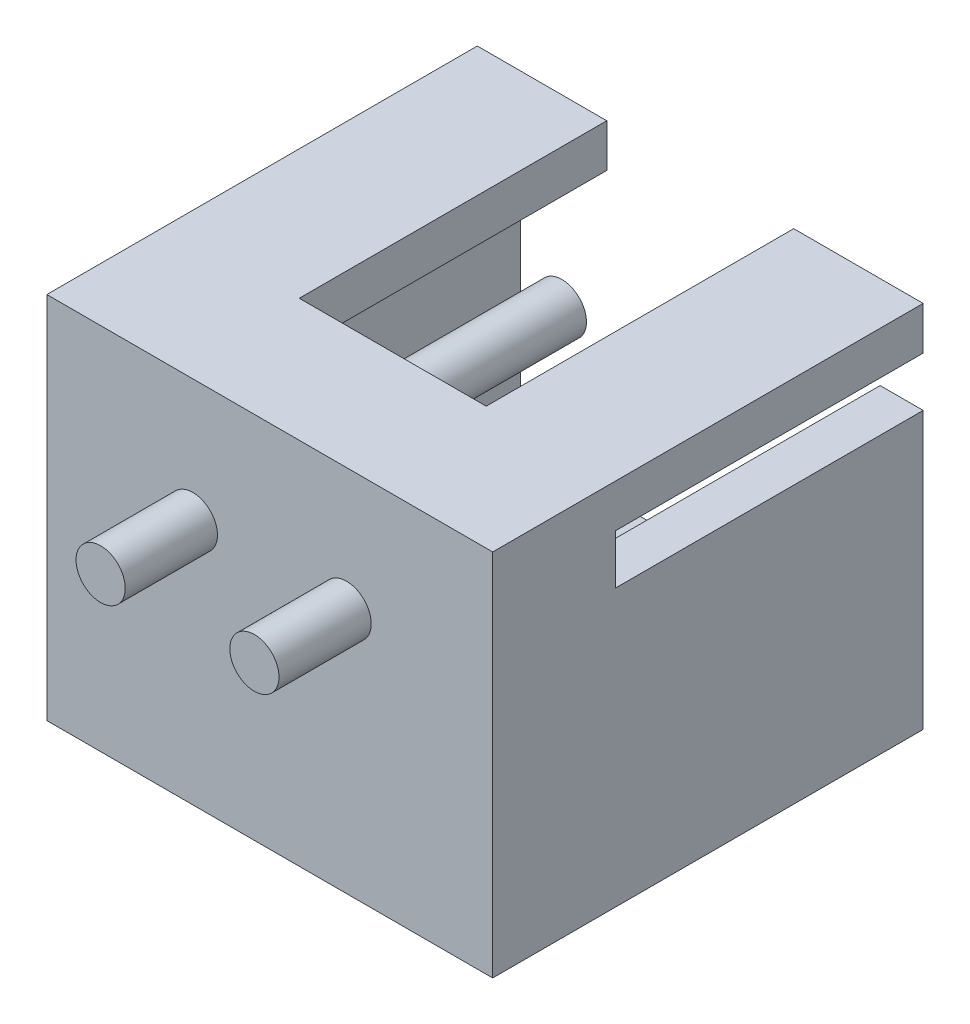
SolidWorks part; units mm, degrees
ref_plane "前视基准面" through (0, 0, 0) normal (0, 0, 1) x (1, 0, 0)
ref_plane "上视基准面" through (0, 0, 0) normal (0, 1, 0) x (1, 0, 0)
ref_plane "右视基准面" through (0, 0, 0) normal (1, 0, 0) x (0, 0, -1)
sketch "草图1" plane through (0, 0, 0) normal (0, 0, 1) x (1, 0, 0)
  line L1 (0, 0) -> (7.25, 0)
  line L2 (0, 0) -> (0, 6)
  line L3 (0, 6) -> (7.25, 6)
  line L4 (7.25, 0) -> (7.25, 6)
  dimension "D1" = 7.25
  dimension "D2" = 6
extrude "凸台-拉伸1" add sketch "草图1" along normal blind 7
sketch "草图2" plane through (0, 0, 0) normal (0, 0, 1) x (1, 0, 0)
  line L0 (0.7, 5.3) -> (6.55, 5.3)
  line L1 (6.55, 5.3) -> (6.55, 0.7)
  line L2 (6.55, 0.7) -> (0.7, 0.7)
  line L3 (0.7, 0.7) -> (0.7, 5.3)
  line L4 (0, 6) -> (0, 0) construction
  line L5 (7.25, 6) -> (0, 6) construction
  line L6 (7.25, 0) -> (7.25, 6) construction
  line L7 (0, 0) -> (7.25, 0) construction
  dimension "D1" = 0.7
  dimension "D2" = 0.7
  dimension "D3" = 0.7
  dimension "D4" = 0.7
extrude "切除-拉伸1" cut sketch "草图2" along normal blind 5
sketch "草图3" plane through (0, 0, 0) normal (0, 0, -1) x (-1, 0, 0)
  line L0 (-3.625, 6) -> (-3.625, 0) construction
  line L1 (-7.25, 6) -> (0, 6) construction
  line L2 (0, 0) -> (-7.25, 0) construction
  line L3 (-7.25, 5.3) -> (-6.55, 5.3)
  line L4 (-7.25, 0) -> (-7.25, 6) construction
  line L5 (0, 6) -> (0, 0) construction
  line L6 (0, 5.3) -> (0, 4.4931)
  line L7 (0, 4.4931) -> (-0.7, 4.4931)
  line L8 (-7.25, 4.4931) -> (-7.25, 5.3)
  line L9 (-5.1449, 6) -> (-5.1449, 5.3)
  line L10 (-2.1051, 6) -> (-2.1051, 5.3)
  line L11 (-5.1449, 6) -> (-2.1051, 6)
  line L12 (-6.55, 5.3) -> (-6.55, 4.4931)
  line L13 (-6.55, 0.7) -> (-6.55, 5.3) construction
  line L14 (-0.7, 5.3) -> (-0.7, 4.4931)
  line L15 (-5.1449, 5.3) -> (-2.1051, 5.3)
  line L16 (-6.55, 4.4931) -> (-7.25, 4.4931)
  line L17 (-0.7, 5.3) -> (0, 5.3)
  dimension "D1" = 0.8069
  dimension "D2" = 3.0398
extrude "切除-拉伸2" cut sketch "草图3" against normal up to surface (5 mm away) up to face at (3.625, 3, 5)
sketch "草图4" plane through (0, 0, 5) normal (0, 0, -1) x (-1, 0, 0)
  line L0 (-3.625, 6) -> (-3.625, 0) construction
  line L1 (-5.1449, 6) -> (-2.1051, 6) construction
  line L2 (0, 0) -> (-7.25, 0) construction
  line L3 (-7.25, 4) -> (0, 4) construction
  line L4 (-7.25, 0) -> (-7.25, 4.4931) construction
  line L5 (0, 4.4931) -> (0, 0) construction
  circle A0 centre (-4.875, 4) radius 0.4
  circle A1 centre (-2.375, 4) radius 0.4
  dimension "D2" = 0.8
  dimension "D3" = 2.5
  dimension "D1" = 2
extrude "凸台-拉伸2" add sketch "草图4" along normal blind 4 and the other way blind 3.5
